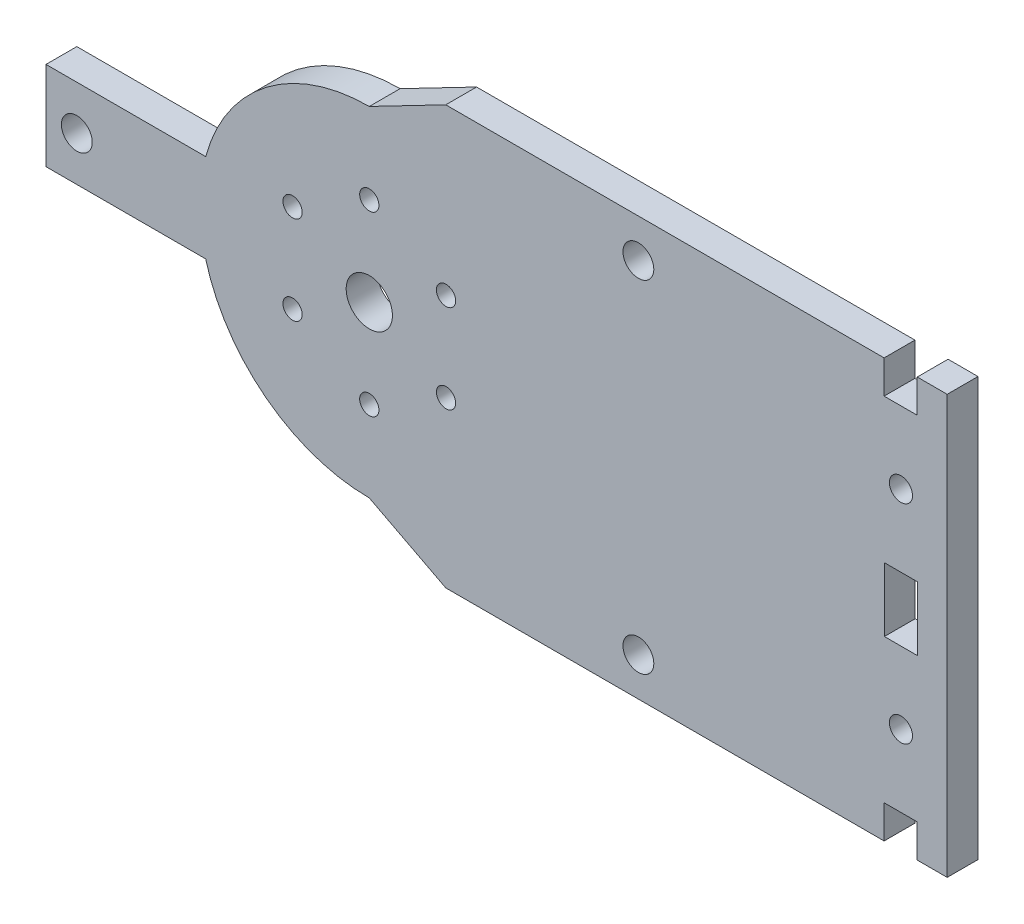
SolidWorks part; units mm, degrees
ref_plane "前视基准面" through (0, 0, 0) normal (0, 0, 1) x (1, 0, 0)
ref_plane "上视基准面" through (0, 0, 0) normal (0, 1, 0) x (1, 0, 0)
ref_plane "右视基准面" through (0, 0, 0) normal (1, 0, 0) x (0, 0, -1)
sketch "草图1" plane through (0, 0, 0) normal (0, 0, 1) x (1, 0, 0)
  line L0 (30.001, 15) -> (30.001, 12) construction
  line L1 (27.8157, 27.15) -> (32.1157, 27.15) construction
  line L2 (32.151, -4.15) -> (27.851, -4.15)
  line L3 (32.151, -4.15) -> (32.151, 4.15)
  line L4 (32.151, 4.15) -> (27.851, 4.15)
  line L5 (27.851, -4.15) -> (27.851, 4.15)
  line L6 (32.151, -4.15) -> (27.851, 4.15) construction
  line L7 (32.151, 4.15) -> (27.851, -4.15) construction
  line L8 (32.1157, 27.15) -> (32.1157, 22.85)
  line L9 (27.8157, 22.85) -> (32.1157, 22.85)
  line L10 (27.8157, 27.15) -> (27.8157, 22.85)
  line L11 (30.001, 0) -> (30.8707, 0) construction
  line L12 (27.8157, -27.15) -> (32.1157, -27.15) construction
  line L13 (30.001, -15) -> (30.001, -12) construction
  line L14 (27.8157, -27.15) -> (27.8157, -22.85)
  line L15 (27.8157, -22.85) -> (32.1157, -22.85)
  line L16 (32.1157, -27.15) -> (32.1157, -22.85)
  line L17 (32.1157, -27.15) -> (36.001, -27.15)
  line L18 (36.001, -27.15) -> (36.001, 27.15)
  line L19 (36.001, 27.15) -> (32.1157, 27.15)
  line L23 (-38.999, -22.002) -> (-29.075, -27.15)
  line L25 (-38.999, 22.002) -> (-29.075, 27.15)
  line L29 (27.8157, -27.15) -> (-29.075, -27.15)
  line L30 (-29.075, 27.15) -> (27.8157, 27.15)
  line L31 (-29.075, -27.15) -> (-29.075, 27.15) construction
  line L34 (-48.9583, 5.75) -> (-48.9583, -5.75) construction
  line L38 (-60.2364, 5.75) -> (-80.9583, 5.75)
  line L39 (-80.9583, -5.75) -> (-60.2364, -5.75)
  line L40 (-80.9583, 5.75) -> (-80.9583, -5.75)
  circle A0 centre (30.001, 13.5) radius 1.5
  circle A1 centre (30.001, -13.5) radius 1.5
  circle A3 centre (-38.999, 0) radius 3
  circle A6 centre (-38.999, 0) radius 11.5 construction
  circle A7 centre (-38.999, -11.5) radius 1.25
  circle A18 centre (-38.999, 0) radius 22.002 construction
  circle A25 centre (-48.9583, -5.75) radius 1.25
  circle A26 centre (-48.9583, 5.75) radius 1.25
  circle A27 centre (-38.999, 11.5) radius 1.25
  circle A28 centre (-29.0397, 5.75) radius 1.25
  circle A29 centre (-29.0397, -5.75) radius 1.25
  circle A30 centre (-4.075, -22.15) radius 2
  circle A31 centre (-4.075, 22.15) radius 2
  arc A32 (-38.999, -22.002) -> (-60.2364, -5.75) centre (-38.999, 0) cw
  arc A33 (-60.2364, 5.75) -> (-38.999, 22.002) centre (-38.999, 0) cw
  circle A34 centre (-76.9583, 0) radius 2
  point P4 (30.001, 0)
  dimension "D3" = 6
  dimension "D4" = 75
  dimension "D5" = 6
  dimension "D6" = 11.5
  dimension "D7" = 23
  dimension "D8" = 2.5
  dimension "D9" = 25
  dimension "D11" = 5
  dimension "D14" = 4
  dimension "D1" = 8.3
  dimension "D2" = 4.3
  dimension "D10" = 5
  dimension "D12" = 25
  dimension "D13" = 28
  dimension "D15" = 3.8853
  dimension "D16" = 4.3
extrude "凸台-拉伸1" add sketch "草图1" along normal blind 4
